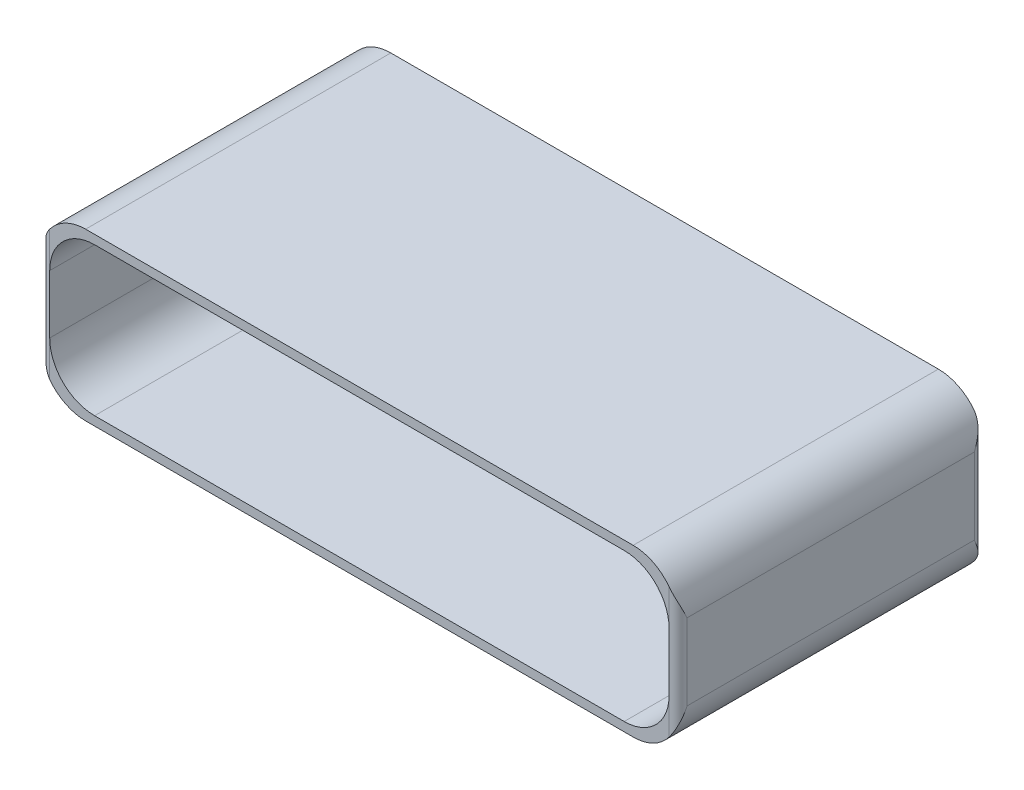
SolidWorks part; units mm, degrees
ref_plane "Front Plane" through (0, 0, 0) normal (0, 0, 1) x (1, 0, 0)
ref_plane "Top Plane" through (0, 0, 0) normal (0, 1, 0) x (1, 0, 0)
ref_plane "Right Plane" through (0, 0, 0) normal (1, 0, 0) x (0, 0, -1)
sketch "Sketch12" plane through (0, 0, 0) normal (0, 0, 1) x (1, 0, 0)
  line L1 (30.5, -9.25) -> (-30.5, -9.25)
  line L2 (35.5, -4.25) -> (35.5, 4.25)
  line L3 (30.5, 9.25) -> (-30.5, 9.25)
  line L4 (-35.5, -4.25) -> (-35.5, 4.25)
  line L5 (35.5, -9.25) -> (-35.5, 9.25) construction
  line L6 (35.5, 9.25) -> (-35.5, -9.25) construction
  line L7 (29.5, -8.25) -> (-29.5, -8.25)
  line L8 (34.5, -3.25) -> (34.5, 3.25)
  line L9 (29.5, 8.25) -> (-29.5, 8.25)
  line L10 (-34.5, -3.25) -> (-34.5, 3.25)
  line L11 (34.5, -8.25) -> (-34.5, 8.25) construction
  line L12 (34.5, 8.25) -> (-34.5, -8.25) construction
  arc A0 (-30.5, 9.25) -> (-35.5, 4.25) centre (-30.5, 4.25) ccw
  arc A1 (-30.5, -9.25) -> (-35.5, -4.25) centre (-30.5, -4.25) cw
  arc A2 (30.5, -9.25) -> (35.5, -4.25) centre (30.5, -4.25) ccw
  arc A3 (35.5, 4.25) -> (30.5, 9.25) centre (30.5, 4.25) ccw
  arc A4 (34.5, 3.25) -> (29.5, 8.25) centre (29.5, 3.25) ccw
  arc A5 (29.5, -8.25) -> (34.5, -3.25) centre (29.5, -3.25) ccw
  arc A6 (-29.5, -8.25) -> (-34.5, -3.25) centre (-29.5, -3.25) cw
  arc A7 (-29.5, 8.25) -> (-34.5, 3.25) centre (-29.5, 3.25) ccw
  point P0 (0, 0)
  point P18 (0, 0)
  dimension "D3" = 5
  dimension "D6" = 5
  dimension "D1" = 71
  dimension "D2" = 18.5
  dimension "D4" = 1
  dimension "D5" = 1
extrude "Boss-Extrude3" add sketch "Sketch12" along normal blind 34
sketch "Sketch14" plane through (0, 0, 0) normal (0, 1, 0) x (1, 0, 0)
  line L0 (-30.5, 0) -> (-35.5, 0) construction
  line L1 (-30.5, 0) -> (-34.5, 0)
  line L2 (-35.5, -34) -> (-35.5, 0) construction
  line L3 (-35.5, -33) -> (-35.5, -1)
  line L4 (-35.5, -34) -> (-30.5, -34) construction
  line L5 (-34.5, -34) -> (-30.5, -34)
  line L6 (30.5, -34) -> (35.5, -34) construction
  line L7 (30.5, -34) -> (34.5, -34)
  line L8 (35.5, -34) -> (35.5, 0) construction
  line L9 (35.5, -33) -> (35.5, -1)
  line L10 (35.5, 0) -> (30.5, 0) construction
  line L11 (34.5, 0) -> (30.5, 0)
  line L12 (30.5, -34) -> (-30.5, -34) construction
  line L13 (30.5, -34) -> (-30.5, -34)
  line L14 (30.5, 0) -> (-30.5, 0) construction
  line L15 (30.5, 0) -> (-30.5, 0)
  line L16 (-35.5, -1) -> (35.5, -1)
  line L17 (-35.5, -33) -> (35.5, -33)
  line L18 (-35.5, -1) -> (-35.5, 0)
  line L19 (-35.5, 0) -> (-34.5, 0)
  line L20 (-35.5, -1) -> (-35.5, 0)
  line L21 (-35.5, 0) -> (-34.5, 0)
  line L22 (-35.5, -33) -> (-35.5, -34)
  line L23 (-35.5, -34) -> (-34.5, -34)
  line L24 (35.5, -33) -> (35.5, -34)
  line L25 (35.5, -34) -> (34.5, -34)
  line L26 (34.5, 0) -> (35.5, 0)
  line L27 (35.5, 0) -> (35.5, -1)
  arc A0 (34.5, 0) -> (35.5, -1) centre (34.5, -1) cw
  arc A1 (34.5, -34) -> (35.5, -33) centre (34.5, -33) ccw
  arc A2 (-35.5, -33) -> (-34.5, -34) centre (-34.5, -33) ccw
  arc A3 (-34.5, 0) -> (-35.5, -1) centre (-34.5, -1) ccw
  dimension "D1" = 1
extrude "Cut-Extrude4" cut sketch "Sketch14" against normal mid plane 34 contours A3 L19 L18 | L26 A0 L27 | A1 L25 L24 | A2 L22 L23
